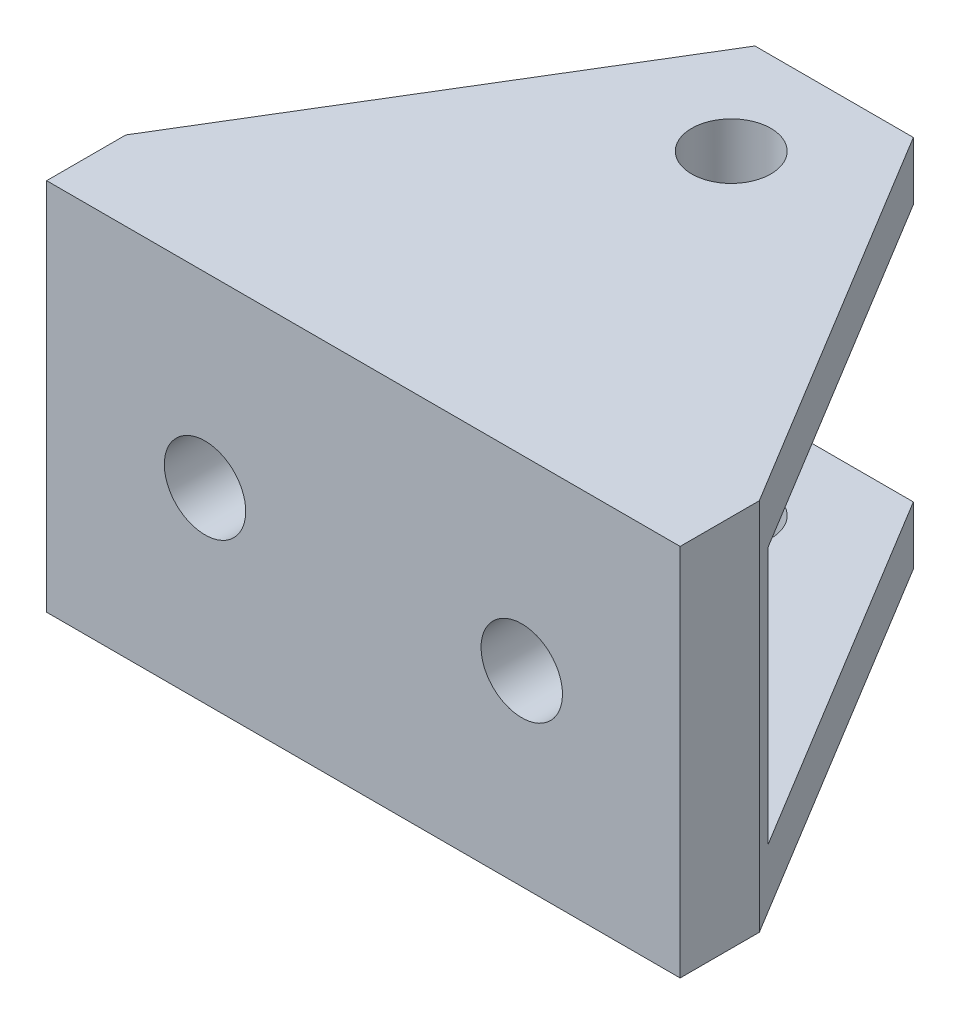
SolidWorks part; units mm, degrees
material "6061-T6 (SS)"
ref_plane "X-Y Datum" through (0, 0, 0) normal (0, 0, 1) x (1, 0, 0)
ref_plane "X-Z Datum" through (0, 0, 0) normal (0, 1, 0) x (1, 0, 0)
ref_plane "Y-Z Datum" through (0, 0, 0) normal (1, 0, 0) x (0, 0, -1)
sketch "Sketch1" plane through (0, 0, 0) normal (1, 0, 0) x (0, 0, -1)
  line L0 (0, 0) -> (0, 29.972)
  line L1 (0, 29.972) -> (39.8563, 29.972)
  line L2 (39.8563, 29.972) -> (39.8563, 25.3111)
  line L3 (39.8563, 25.3111) -> (8.1063, 25.3111)
  line L4 (8.1063, 25.3111) -> (8.1063, 4.6609)
  line L5 (8.1063, 4.6609) -> (39.8563, 4.6609)
  line L6 (39.8563, 4.6609) -> (39.8563, 0)
  line L7 (39.8563, 0) -> (0, 0)
  line L8 (27.1563, 29.972) -> (27.1563, 0) construction
  dimension "D1" = 20.6502
  dimension "D2" = 12.7
  dimension "D3" = 31.75
  dimension "D4" = 29.972
extrude "Boss-Extrude1" add sketch "Sketch1" along normal blind 50.8
sketch "Sketch2" plane through (0, 0, -8.1063) normal (0, 0, -1) x (-1, 0, 0)
  line L0 (-25.4, 25.3111) -> (-25.4, 4.6609) construction
  line L1 (-50.8, 25.3111) -> (0, 25.3111) construction
  line L2 (-50.8, 4.6609) -> (0, 4.6609) construction
  line L3 (-38.1, 14.986) -> (-12.7, 14.986) construction
  point P8 (-25.4, 14.986)
  point P9 (-25.4, 14.986)
  point P11 (-38.1, 14.986)
  point P12 (-12.7, 14.986)
  dimension "D1" = 25.4
hole_wizard "CBORE for 1/4 Binding Head Machine Screw1" positions "Sketch2" profile "Sketch3" counterbore size "1/4" standard "ANSI Inch" end condition through all
sketch "Sketch3" plane through (12.7, 14.986, -8.1063) normal (1, 0, 0) x (0, 1, 0)
  line L0 (0, 0) -> (0, 8.1063)
  line L1 (0, 8.1063) -> (3.2639, 8.1063)
  line L3 (3.2639, 8.1063) -> (3.2639, 3.302)
  line L4 (3.2639, 3.302) -> (7.1437, 3.302)
  line L5 (7.1437, 3.302) -> (7.1437, 0)
  line L7 (7.1437, 0) -> (0, 0)
  line L11 (0, -6.35) -> (0, 107.95) construction
  dimension "Thru Hole Dia." = 6.5278
  dimension "Thru Hole Depth" = 8.1063
  dimension "C'Bore Dia." = 14.2875
  dimension "C'Bore Depth" = 3.302
sketch "Sketch4" plane through (0, 0, 0) normal (0, -1, 0) x (1, 0, 0)
  line L0 (25.4, -39.8563) -> (25.4, 0) construction
  line L1 (50.8, -39.8563) -> (0, -39.8563) construction
  line L2 (50.8, 0) -> (0, 0) construction
  line L3 (0, -6.35) -> (19.05, -37.7528)
  line L4 (50.8, -6.35) -> (31.75, -37.7528)
  line L5 (0, -6.35) -> (0, -39.8563)
  line L6 (0, -39.8563) -> (50.8, -39.8563)
  line L7 (50.8, -39.8563) -> (50.8, -6.35)
  line L8 (0, 0) -> (0, -39.8563) construction
  line L9 (50.8, 0) -> (50.8, -39.8563) construction
  line L10 (19.05, -37.7528) -> (31.75, -37.7528)
  circle A0 centre (25.4, -29.4978) radius 3.175
  point P8 (39.8222, -35.5789)
  point P22 (0, -17.9921)
  dimension "D1" = 6.35
  dimension "D2" = 5.08
  dimension "D3" = 6.35
  dimension "D4" = 12.7
extrude "Cut-Extrude1" cut sketch "Sketch4" against normal up to surface (29.972 mm away) up to face at (25.4, 29.972, -19.9282)
